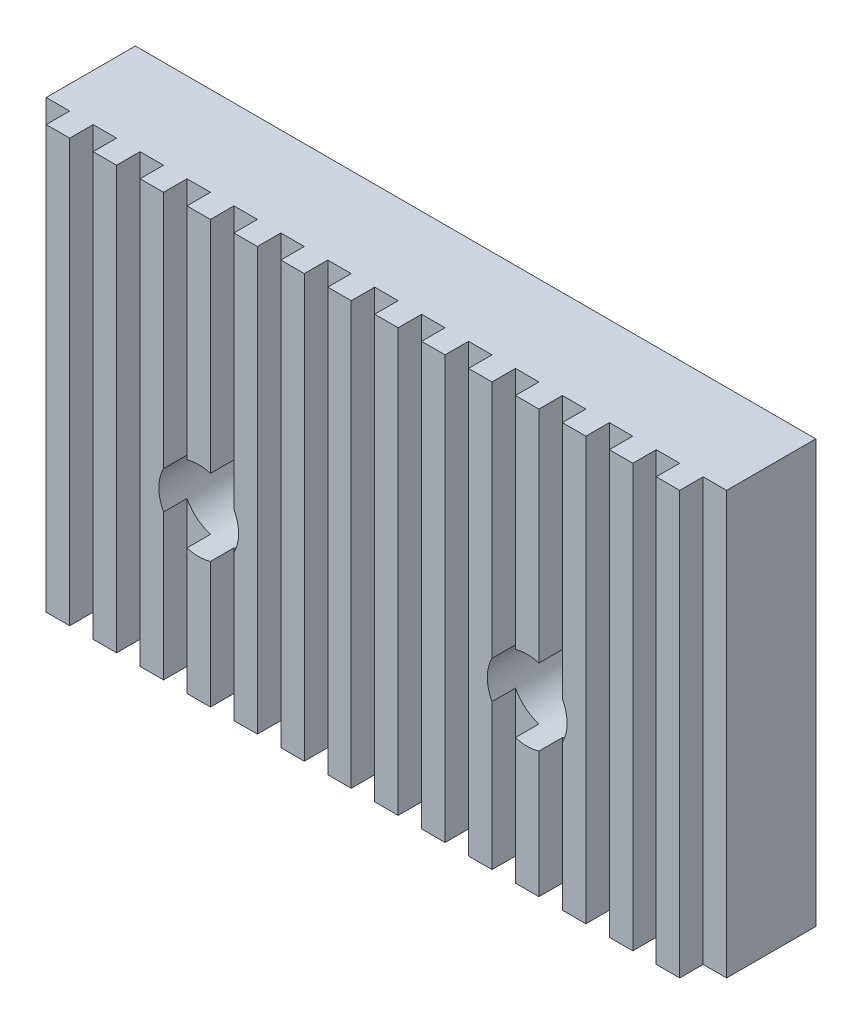
SolidWorks part; units mm, degrees
ref_plane "前视基准面" through (0, 0, 0) normal (0, 0, 1) x (1, 0, 0)
ref_plane "上视基准面" through (0, 0, 0) normal (0, 1, 0) x (1, 0, 0)
ref_plane "右视基准面" through (0, 0, 0) normal (1, 0, 0) x (0, 0, -1)
other "Configuration Table"
sketch "草图1" plane through (0, 0, 0) normal (0, 0, 1) x (1, 0, 0)
  line L0 (-17.8041, 7) -> (43.6885, 7) construction
  line L1 (0, 0) -> (29, 0)
  line L2 (0, 0) -> (0, 18)
  line L3 (0, 18) -> (29, 18)
  line L4 (29, 0) -> (29, 18)
  line L5 (14.5, 31.3774) -> (14.5, -6.4209) construction
  circle A0 centre (21.5, 7) radius 1.7
  circle A1 centre (7.5, 7) radius 1.7
  dimension "D4" = 3.4
  dimension "D1" = 7
  dimension "D2" = 11
  dimension "D3" = 29
  dimension "D5" = 14
extrude "凸台-拉伸1" add sketch "草图1" along normal blind 4.8
sketch "草图2" plane through (0, 18, 0) normal (0, 1, 0) x (1, 0, 0)
  line L0 (14.5, -4.8) -> (14.5, 3.6867) construction
  line L1 (29, -4.8) -> (0, -4.8) construction
  line L2 (14.5, -3.8) -> (14, -3.8)
  line L3 (14, -3.8) -> (14, -4.8)
  line L4 (14, -4.8) -> (13, -4.8)
  line L5 (13, -4.8) -> (13, -3.8)
  line L6 (13, -3.8) -> (12.5, -3.8)
  line L7 (12, -3.8) -> (12, -4.8)
  line L8 (12.5, -3.8) -> (12, -3.8)
  line L9 (11, -4.8) -> (11, -3.8)
  line L10 (11, -3.8) -> (10.5, -3.8)
  line L11 (12, -4.8) -> (11, -4.8)
  line L12 (10, -3.8) -> (10, -4.8)
  line L13 (10.5, -3.8) -> (10, -3.8)
  line L14 (9, -4.8) -> (9, -3.8)
  line L15 (9, -3.8) -> (8.5, -3.8)
  line L16 (10, -4.8) -> (9, -4.8)
  line L17 (8, -3.8) -> (8, -4.8)
  line L18 (8.5, -3.8) -> (8, -3.8)
  line L19 (7, -4.8) -> (7, -3.8)
  line L20 (7, -3.8) -> (6.5, -3.8)
  line L21 (8, -4.8) -> (7, -4.8)
  line L22 (6, -3.8) -> (6, -4.8)
  line L23 (6.5, -3.8) -> (6, -3.8)
  line L24 (5, -4.8) -> (5, -3.8)
  line L25 (5, -3.8) -> (4.5, -3.8)
  line L26 (6, -4.8) -> (5, -4.8)
  line L27 (4, -3.8) -> (4, -4.8)
  line L28 (4.5, -3.8) -> (4, -3.8)
  line L29 (3, -4.8) -> (3, -3.8)
  line L30 (3, -3.8) -> (2.5, -3.8)
  line L31 (4, -4.8) -> (3, -4.8)
  line L32 (2, -3.8) -> (2, -4.8)
  line L33 (2.5, -3.8) -> (2, -3.8)
  line L34 (1, -4.8) -> (1, -3.8)
  line L35 (1, -3.8) -> (0.5, -3.8)
  line L36 (2, -4.8) -> (1, -4.8)
  line L37 (0.5, -3.8) -> (0, -3.8)
  line L38 (0, -4.8) -> (0, 0) construction
  line L39 (16, -3.8) -> (16, -4.8)
  line L40 (15, -4.8) -> (15, -3.8)
  line L41 (16, -4.8) -> (15, -4.8)
  line L42 (16.5, -3.8) -> (16, -3.8)
  line L43 (15, -3.8) -> (14.5, -3.8)
  line L44 (18, -3.8) -> (18, -4.8)
  line L45 (17, -4.8) -> (17, -3.8)
  line L46 (18, -4.8) -> (17, -4.8)
  line L47 (18.5, -3.8) -> (18, -3.8)
  line L48 (17, -3.8) -> (16.5, -3.8)
  line L49 (20, -3.8) -> (20, -4.8)
  line L50 (19, -4.8) -> (19, -3.8)
  line L51 (20, -4.8) -> (19, -4.8)
  line L52 (20.5, -3.8) -> (20, -3.8)
  line L53 (19, -3.8) -> (18.5, -3.8)
  line L54 (22, -3.8) -> (22, -4.8)
  line L55 (21, -4.8) -> (21, -3.8)
  line L56 (22, -4.8) -> (21, -4.8)
  line L57 (22.5, -3.8) -> (22, -3.8)
  line L58 (21, -3.8) -> (20.5, -3.8)
  line L59 (24, -3.8) -> (24, -4.8)
  line L60 (23, -4.8) -> (23, -3.8)
  line L61 (24, -4.8) -> (23, -4.8)
  line L62 (24.5, -3.8) -> (24, -3.8)
  line L63 (23, -3.8) -> (22.5, -3.8)
  line L64 (26, -3.8) -> (26, -4.8)
  line L65 (25, -4.8) -> (25, -3.8)
  line L66 (26, -4.8) -> (25, -4.8)
  line L67 (26.5, -3.8) -> (26, -3.8)
  line L68 (25, -3.8) -> (24.5, -3.8)
  line L69 (28, -3.8) -> (28, -4.8)
  line L70 (27, -4.8) -> (27, -3.8)
  line L71 (28, -4.8) -> (27, -4.8)
  line L72 (28.5, -3.8) -> (28, -3.8)
  line L73 (27, -3.8) -> (26.5, -3.8)
  line L74 (28.5, -3.8) -> (29, -3.8)
  line L75 (29, -4.8) -> (29, 0) construction
  line L76 (0, -3.8) -> (0, -4.8)
  line L77 (0, -4.8) -> (29, -4.8)
  line L78 (29, -4.8) -> (29, -3.8)
  line M38 (0, 0) -> (0, -4.8)
  line M39 (0, -4.8) -> (29, -4.8)
  line M40 (29, -4.8) -> (29, 0)
  dimension "D1" = 0.5
  dimension "D2" = 1
  dimension "D3" = 1
  dimension "D4" = 7
  dimension "D5" = 8
extrude "切除-拉伸1" cut sketch "草图2" against normal through all contours L35 L37 L34 M38 M39 | L30 L33 L32 L29 M39 | L25 L28 L27 L24 M39 | L20 L23 L22 L19 M39 | L15 L18 L17 L14 M39 | L10 L13 L12 L9 M39 | L6 L8 L7 L5 M39 | L0 L77 L40 L43 | L0 L2 L3 M39 | L45 L48 L42 L39 M39 | L50 L53 L47 L44 M39 | L55 L58 L52 L49 M39 | L60 L63 L57 L54 M39 | L65 L68 L62 L59 M39 | L70 L73 L67 L64 M39 | L74 L72 L69 M39 M40
